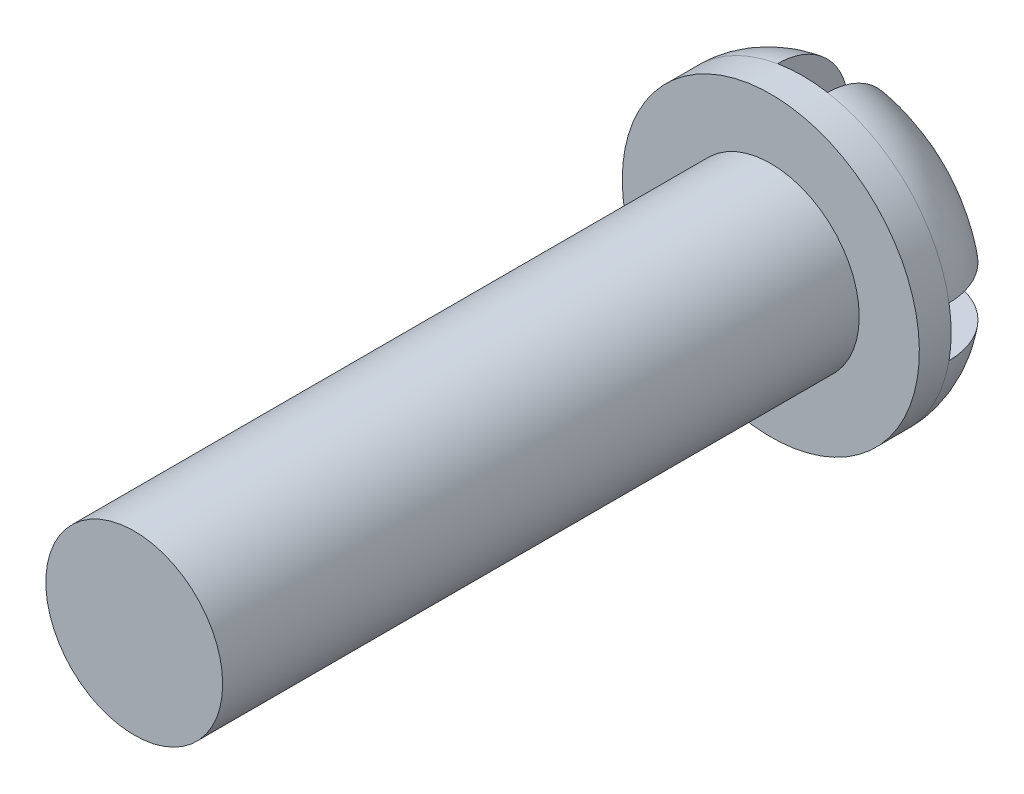
SolidWorks part; units mm, degrees
ref_plane "前视基准面" through (0, 0, 0) normal (0, 0, 1) x (1, 0, 0)
ref_plane "上视基准面" through (0, 0, 0) normal (0, 1, 0) x (1, 0, 0)
ref_plane "右视基准面" through (0, 0, 0) normal (1, 0, 0) x (0, 0, -1)
sketch "草图1" plane through (0, 0, 0) normal (0, 0, 1) x (1, 0, 0)
  circle A0 centre (0, 0) radius 2.5
  dimension "D1" = 5
extrude "凸台-拉伸1" add sketch "草图1" along normal blind 18
sketch "草图2" plane through (0, 0, 0) normal (0, 0, -1) x (-1, 0, 0)
  circle A0 centre (0, 0) radius 4.2
  dimension "D1" = 8.4
extrude "凸台-拉伸2" add sketch "草图2" along normal blind 2.9
fillet "圆角1" radius 2 1 edges at (-4.2, 0, -2.9)
sketch "草图3" plane through (0, 0, -2.9) normal (0, 0, -1) x (-1, 0, 0)
  line L0 (-0.7071, 0.7071) -> (-0.7071, 6.0064)
  line L1 (1, -1) -> (-1, -1) construction
  line L2 (1, -1) -> (1, 1) construction
  line L3 (1, 1) -> (-1, 1) construction
  line L4 (-1, -1) -> (-1, 1) construction
  line L5 (1, -1) -> (-1, 1) construction
  line L6 (1, 1) -> (-1, -1) construction
  line L7 (0.7071, 0.7071) -> (0.7071, 6.0064)
  line L8 (0.7071, 6.0064) -> (-0.7071, 6.0064)
  line L9 (0.7071, 0.7071) -> (6.0064, 0.7071)
  line L10 (0.7071, -0.7071) -> (6.0064, -0.7071)
  line L11 (6.0064, -0.7071) -> (6.0064, 0.7071)
  line L12 (0.7071, -0.7071) -> (0.7071, -6.0064)
  line L13 (-0.7071, -0.7071) -> (-0.7071, -6.0064)
  line L14 (-0.7071, -6.0064) -> (0.7071, -6.0064)
  line L15 (-0.7071, -0.7071) -> (-6.0064, -0.7071)
  line L16 (-0.7071, 0.7071) -> (-6.0064, 0.7071)
  line L17 (-6.0064, 0.7071) -> (-6.0064, -0.7071)
  circle A0 centre (0, 0) radius 1 construction
  dimension "D1" = 4
extrude "切除-拉伸1" cut sketch "草图3" against normal blind 2
